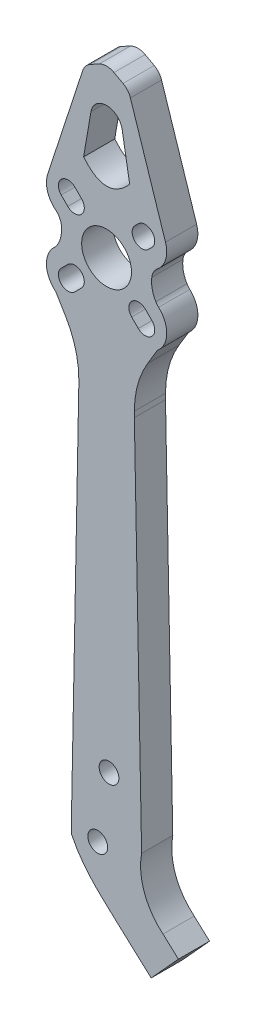
SolidWorks part; units mm, degrees
ref_plane "Alzado" through (0, 0, 0) normal (0, 0, 1) x (1, 0, 0)
ref_plane "Planta" through (0, 0, 0) normal (0, 1, 0) x (1, 0, 0)
ref_plane "Vista lateral" through (0, 0, 0) normal (1, 0, 0) x (0, 0, -1)
sketch "Croquis1" plane through (0, 0, 0) normal (0, 0, 1) x (1, 0, 0)
  line L0 (-3.6902, 12.1812) -> (-2.5021, 19.0797)
  line L5 (1.4432, 0) -> (-1.4432, 0) construction
  line L6 (0, 26.6547) -> (0, 27) construction
  line L7 (-9.4591, 6.8989) -> (-3.8261, 24.1432)
  line L8 (-2.6434, 25.5635) -> (-1.1937, 26.3513)
  line L9 (2.6434, 25.5635) -> (1.1937, 26.3513)
  line L10 (9.4591, 6.8989) -> (3.8261, 24.1432)
  line L11 (-4.4598, -19.1024) -> (-4.4598, -20)
  line L12 (-6.609, -11.3656) -> (-8.1748, -8.7649)
  line L13 (0, 33.6082) -> (0, 9.9689)
  line L15 (6.609, -11.3656) -> (8.1748, -8.7649)
  line L16 (-4.4598, -20) -> (-5.6262, -80)
  line L23 (0, 4) -> (2.2899, 4) construction
  line L25 (3.7077, 12.0797) -> (2.5021, 19.0797)
  line L26 (0, 0) -> (0, -80) construction
  line L27 (4.4598, -20) -> (5.6262, -80)
  line L28 (4.4598, -19.1024) -> (4.4598, -20)
  line L29 (-5.6262, -80) -> (5.6262, -80) construction
  line L31 (-5.6262, -80) -> (-5.6262, -82.9587)
  line L34 (11.5353, -91.756) -> (7.1605, -96.5634)
  line L36 (58.4904, -38.7465) -> (-59.2929, -168.1765) construction
  line L37 (7.1605, -96.5634) -> (1.3396, -91.2663)
  line L38 (11.5353, -91.756) -> (9.0583, -89.4964)
  line L39 (-6.1872, 6.1872) -> (-5.1265, 5.1265) construction
  line L40 (-5.0912, 7.2832) -> (-4.0305, 6.2225)
  line L41 (-7.2832, 5.0912) -> (-6.2225, 4.0305)
  line L42 (6.1872, 6.1872) -> (5.1265, 5.1265) construction
  line L47 (-1, 1) -> (1, -1) construction
  line L48 (-1, -1) -> (1, 1) construction
  line L49 (5.0912, 7.2832) -> (4.0305, 6.2225)
  line L50 (7.2832, 5.0912) -> (6.2225, 4.0305)
  line L51 (-6.1872, -6.1872) -> (-5.1265, -5.1265) construction
  line L52 (-5.0912, -7.2832) -> (-4.0305, -6.2225)
  line L53 (-7.2832, -5.0912) -> (-6.2225, -4.0305)
  line L54 (6.1872, -6.1872) -> (5.1265, -5.1265) construction
  line L55 (5.0912, -7.2832) -> (4.0305, -6.2225)
  line L56 (7.2832, -5.0912) -> (6.2225, -4.0305)
  arc A0 (-6.7529, 4.5608) -> (-6.6415, 4.4598) centre (-5.6569, 5.6569) ccw
  circle A1 centre (-5.6569, -5.6569) radius 1.55
  circle A2 centre (5.6569, -5.6569) radius 1.55
  circle A3 centre (5.6569, 5.6569) radius 1.55
  circle A5 centre (0, 0) radius 4
  arc A6 (8.1709, 2.5456) -> (9.4591, 6.8989) centre (5.6569, 5.6569) ccw
  arc A7 (-8.1709, 2.5456) -> (-9.4591, 6.8989) centre (-5.6569, 5.6569) cw
  arc A8 (8.3591, -2.7076) -> (8.1748, -8.7649) centre (5.6569, -5.6569) cw
  arc A9 (-8.3591, -2.7076) -> (-8.1748, -8.7649) centre (-5.6569, -5.6569) ccw
  arc A10 (-7.9055, -2.1526) -> (-7.2631, 0.9247) centre (-11.9961, 0.3069) ccw
  arc A11 (-6.6415, -4.4598) -> (-4.4598, -6.6415) centre (0, 0) ccw
  arc A12 (7.9055, -2.1526) -> (7.2631, 0.9247) centre (11.9961, 0.3069) cw
  arc A14 (4.4598, -6.6415) -> (6.6415, -4.4598) centre (0, 0) ccw
  arc A15 (6.6415, 4.4598) -> (4.4598, 6.6415) centre (0, 0) ccw
  arc A16 (-5.6569, 5.6569) -> (-6.6415, 4.4598) centre (0, 0) ccw
  arc A17 (8.1709, 2.5456) -> (7.2631, 0.9247) centre (9.7421, 0.6011) ccw
  arc A18 (7.9055, -2.1526) -> (8.3591, -2.7076) centre (10.048, -0.8644) ccw
  arc A19 (-7.9055, -2.1526) -> (-8.3591, -2.7076) centre (-10.048, -0.8644) cw
  arc A20 (-8.1709, 2.5456) -> (-7.2631, 0.9247) centre (-9.7421, 0.6011) cw
  arc A21 (2.6434, 25.5635) -> (3.8261, 24.1432) centre (1.4497, 23.3669) cw
  arc A22 (1.1937, 26.3513) -> (-1.1937, 26.3513) centre (0, 24.1547) ccw
  arc A23 (-2.6434, 25.5635) -> (-3.8261, 24.1432) centre (-1.4497, 23.3669) ccw
  arc A24 (-4.4598, -19.1024) -> (-6.609, -11.3656) centre (-19.4598, -19.1024) ccw
  arc A28 (2.5021, 19.0797) -> (-2.5021, 19.0797) centre (0, 18.6488) ccw
  arc A32 (4.4598, -19.1024) -> (6.609, -11.3656) centre (19.4598, -19.1024) cw
  arc A33 (9.0583, -89.4964) -> (5.6262, -80) centre (15.4603, -81.8143) cw
  circle A34 centre (-1.4162, -81.9187) radius 1.59
  circle A35 centre (0.3927, -71.3877) radius 1.5875
  arc A36 (-5.0912, 7.2832) -> (-7.2832, 5.0912) centre (-6.1872, 6.1872) ccw
  arc A37 (-6.2225, 4.0305) -> (-4.0305, 6.2225) centre (-5.1265, 5.1265) ccw
  arc A38 (-4.4598, 6.6415) -> (-4.5608, 6.7529) centre (-5.6569, 5.6569) ccw
  arc A39 (5.0912, 7.2832) -> (7.2832, 5.0912) centre (6.1872, 6.1872) cw
  arc A40 (6.2225, 4.0305) -> (4.0305, 6.2225) centre (5.1265, 5.1265) cw
  arc A41 (-5.0912, -7.2832) -> (-7.2832, -5.0912) centre (-6.1872, -6.1872) cw
  arc A42 (-6.2225, -4.0305) -> (-4.0305, -6.2225) centre (-5.1265, -5.1265) cw
  arc A43 (5.0912, -7.2832) -> (7.2832, -5.0912) centre (6.1872, -6.1872) ccw
  arc A44 (6.2225, -4.0305) -> (4.0305, -6.2225) centre (5.1265, -5.1265) ccw
  spline S0 degree 2 poles (-3.6902, 12.1812) (-0.0399, 7.8077) (3.7077, 12.0797) knots 0 0 0 1 1 1
  spline S1 degree 3 poles (-5.6262, -82.9587) (-3.958, -86.469) (-1.2928, -88.8487) (1.5095, -91.4223) (1.5956, -91.4992) knots 0 0 0 0 0.775056 0.79931 0.79931 0.79931 0.79931
  point P46 (7.5969, 2.1588)
  point P49 (8.1666, -2.5422)
  point P52 (-8.1666, -2.5422)
  point P55 (-7.5969, 2.1588)
  point P58 (3.5173, 25.0886)
  point P64 (-3.5173, 25.0886)
  point P77 (4.2446, 10.2207)
  point P81 (-4.2446, 10.2207)
  point P95 (-5.6569, 5.6569)
  point P109 (5.6569, 5.6569)
  point P116 (-5.6569, -5.6569)
  point P123 (5.6569, -5.6569)
  dimension "D1" = 3.1
  dimension "D4" = 23
  dimension "D3" = 8
  dimension "D7" = 2.5
  dimension "D8" = 15
  dimension "D9" = 7
  dimension "D13" = 6.5
  dimension "D14" = 10
  dimension "D12" = 80
  dimension "D17" = 2.9587
  dimension "D18" = 2.8864
  dimension "D19" = 45
  dimension "D2" = 16
  dimension "D5" = 11.3137
  dimension "D6" = 12
  dimension "D10" = 7
  dimension "D11" = 5.6262
  dimension "D15" = 2
  dimension "D16" = 2
  dimension "D20" = 60
  dimension "D21" = 1.5
extrude "Saliente-Extruir1" add sketch "Croquis1" along normal blind 5
sketch "Croquis2" plane through (0, 0, 5) normal (0, 0, 1) x (1, 0, 0)
  circle A0 centre (0, 0) radius 4
